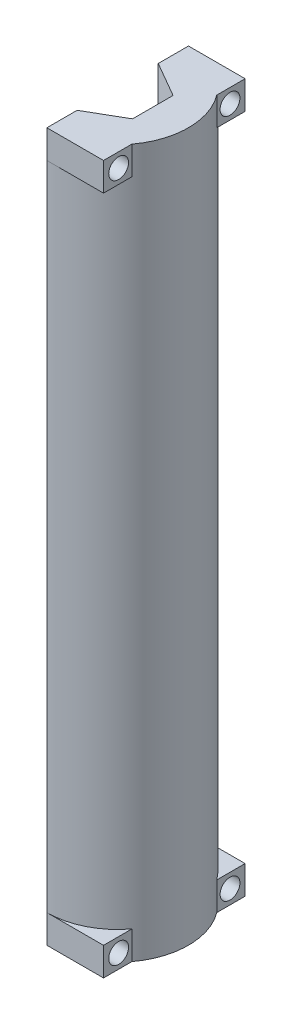
SolidWorks part; units mm, degrees
ref_plane "Front Plane" through (0, 0, 0) normal (0, 0, 1) x (1, 0, 0)
ref_plane "Top Plane" through (0, 0, 0) normal (0, 1, 0) x (1, 0, 0)
ref_plane "Right Plane" through (0, 0, 0) normal (1, 0, 0) x (0, 0, -1)
sketch "Sketch1" plane through (0, 0, 0) normal (0, 1, 0) x (1, 0, 0)
  line L0 (0, 4.2955) -> (0, -4.2955) construction
  line L1 (0, 7.5) -> (0, 4.2955)
  line L2 (0, -4.2955) -> (0, -7.5)
  line L4 (0, -4.2955) -> (3.72, -2.1477)
  line L5 (3.72, -2.1477) -> (3.72, 2.1477)
  line L6 (3.72, 2.1477) -> (0, 4.2955)
  line L8 (0.3615, 4.5042) -> (-4.0815, 1.939) [skipped]
  line L9 (-3.72, 2.5652) -> (-3.72, -2.5652) [skipped]
  line L10 (-4.0815, -1.939) -> (0.3615, -4.5042) [skipped]
  arc A0 (0, 7.5) -> (0, -7.5) centre (0, 0) cw
  dimension "D1" = 15
  dimension "D2" = 3.72
extrude "Main Body" add sketch "Sketch1" along normal blind 75
sketch "Sketch2" plane through (0, 0, 0) normal (-1, 0, 0) x (0, 0, 1)
  line L0 (-4.2955, 75) -> (-4.2955, 0) construction
  line L1 (-7.5, 0) -> (-4.2955, 0)
  line L2 (-7.5, 0) -> (-7.5, 3)
  line L3 (-7.5, 3) -> (-4.2955, 3)
  line L4 (-4.2955, 0) -> (-4.2955, 3)
  line L6 (-7.5, 75) -> (-4.2955, 75)
  line L7 (-7.5, 75) -> (-7.5, 72)
  line L8 (-7.5, 72) -> (-4.2955, 72)
  line L9 (-4.2955, 75) -> (-4.2955, 72)
  dimension "D1" = 3
  dimension "D2" = 3
extrude "Back Screw Holes Support" add sketch "Sketch2" against normal blind 6
sketch "Sketch3" plane through (0, 0, 0) normal (-1, 0, 0) x (0, 0, 1)
  line L0 (-7.5, 73.5) -> (-4.2955, 73.5) construction
  line L1 (-7.5, 75) -> (-7.5, 72) construction
  line L2 (-4.2955, 75) -> (-4.2955, 0) construction
  line L3 (-7.5, 1.5) -> (-4.2955, 1.5) construction
  line L4 (-7.5, 3) -> (-7.5, 0) construction
  circle A0 centre (-5.8977, 73.5) radius 1.05
  circle A1 centre (-5.8977, 1.5) radius 1.05
  dimension "D1" = 2.1
  dimension "D2" = 2.1
extrude "Back Screw Holes" cut sketch "Sketch3" against normal through all
mirror "Front Screw Holes and Support" about plane through (0, 0, 0) normal (0, 0, 1) of "Back Screw Holes", "Back Screw Holes Support"
